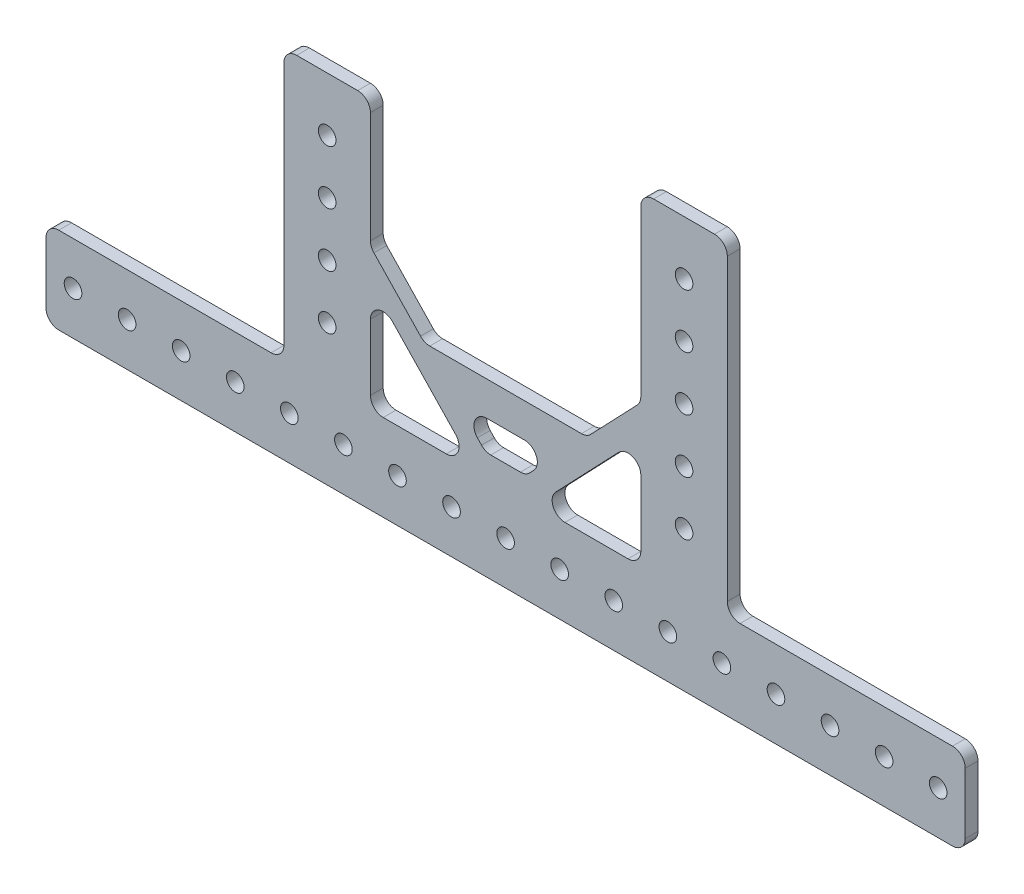
SolidWorks part; units mm, degrees
ref_plane "Front Plane" through (0, 0, 0) normal (0, 0, 1) x (1, 0, 0)
ref_plane "Top Plane" through (0, 0, 0) normal (0, 1, 0) x (1, 0, 0)
ref_plane "Right Plane" through (0, 0, 0) normal (1, 0, 0) x (0, 0, -1)
sketch "Sketch1" plane through (0, 0, 0) normal (0, 0, 1) x (1, 0, 0)
  line L0 (-52.07, 10.16) -> (-31.75, 10.16) construction
  line L1 (-107.95, 10.16) -> (-52.07, 10.16)
  line L2 (-107.95, 10.16) -> (-107.95, -10.16)
  line L3 (-107.95, -10.16) -> (107.95, -10.16)
  line L4 (107.95, 10.16) -> (107.95, -10.16)
  line L5 (-107.95, 10.16) -> (107.95, -10.16) construction
  line L6 (-107.95, -10.16) -> (107.95, 10.16) construction
  line L7 (-52.07, 73.66) -> (-31.75, 73.66)
  line L8 (-52.07, 73.66) -> (-52.07, 10.16)
  line L9 (-52.07, 10.16) -> (-31.75, 10.16) construction
  line L10 (-31.75, 73.66) -> (-31.75, 10.16)
  line L11 (31.75, 86.36) -> (52.07, 86.36)
  line L12 (31.75, 86.36) -> (31.75, 10.16)
  line L13 (31.75, 10.16) -> (52.07, 10.16) construction
  line L14 (52.07, 86.36) -> (52.07, 10.16)
  line L15 (-31.75, 10.16) -> (31.75, 10.16)
  line L16 (31.75, 10.16) -> (52.07, 10.16) construction
  line L17 (52.07, 10.16) -> (107.95, 10.16)
  line L18 (-41.91, 10.16) -> (-41.91, 73.66) construction
  line L19 (0, -55) -> (0, 55) construction
  circle A0 centre (0, 0) radius 2.07
  circle A1 centre (12.7, 0) radius 2.07
  circle A2 centre (25.4, 0) radius 2.07
  circle A3 centre (38.1, 0) radius 2.07
  circle A4 centre (50.8, 0) radius 2.07
  circle A5 centre (63.5, 0) radius 2.07
  circle A6 centre (76.2, 0) radius 2.07
  circle A7 centre (88.9, 0) radius 2.07
  circle A8 centre (101.6, 0) radius 2.07
  circle A9 centre (-12.7, 0) radius 2.07
  circle A10 centre (-25.4, 0) radius 2.07
  circle A11 centre (-38.1, 0) radius 2.07
  circle A12 centre (-50.8, 0) radius 2.07
  circle A13 centre (-63.5, 0) radius 2.07
  circle A14 centre (-76.2, 0) radius 2.07
  circle A15 centre (-88.9, 0) radius 2.07
  circle A16 centre (-101.6, 0) radius 2.07
  circle A17 centre (-41.91, 60.96) radius 2.07
  circle A20 centre (41.91, 60.96) radius 2.07
  circle A21 centre (-41.91, 48.26) radius 2.07
  circle A22 centre (41.91, 48.26) radius 2.07
  circle A23 centre (-41.91, 35.56) radius 2.07
  circle A24 centre (41.91, 35.56) radius 2.07
  circle A25 centre (-41.91, 22.86) radius 2.07
  circle A26 centre (41.91, 22.86) radius 2.07
  circle A27 centre (41.91, 73.66) radius 2.07
  dimension "D1" = 4.14
  dimension "D2" = 20.32
  dimension "D3" = 215.9
  dimension "D4" = 63.5
  dimension "D5" = 31.75
  dimension "D6" = 63.5
  dimension "D8" = 12.7
  dimension "D10" = 12.7
  dimension "D11" = 12.7
  dimension "D13" = 12.7
  dimension "D14" = 76.2
  dimension "D15" = 12.7
  dimension "D7" = 9
  dimension "D9" = 9
  dimension "D12" = 4
extrude "Boss-Extrude1" add sketch "Sketch1" along normal mid plane 3
fillet "Fillet3" radius 3 10 edges at (107.95, -10.16, 0) (-107.95, -10.16, 0) (-107.95, 10.16, 0) (-52.07, 10.16, 0) (-31.75, 10.16, 0) (31.75, 10.16, 0) (52.07, 86.36, 0) (52.07, 10.16, 0) (107.95, 10.16, 0) (-52.07, 73.66, 0)
sketch "Sketch3" plane through (0, 0, 1.5) normal (0, 0, 1) x (1, 0, 0)
  line L0 (-31.75, 43.41) -> (0, 10.16)
  line L1 (-31.75, 13.16) -> (-31.75, 73.66) construction
  line L2 (28.75, 10.16) -> (-28.75, 10.16) construction
  line L3 (0, 10.16) -> (31.75, 43.41)
  line L4 (31.75, 86.36) -> (31.75, 13.16) construction
  line L5 (31.75, 43.41) -> (31.75, 36.17)
  line L6 (6.9134, 10.16) -> (-6.9134, 10.16)
  line L7 (-31.75, 13.16) -> (-31.75, 43.41)
  line L8 (-31.75, 36.17) -> (-6.9134, 10.16)
  line L9 (6.9134, 10.16) -> (31.75, 36.17)
  line L10 (-35.3662, 39.957) -> (-31.75, 36.17) construction
  line L11 (-35.3662, 39.957) -> (0, 2.92) construction
  line L12 (31.75, 36.17) -> (35.3662, 39.957) construction
  line L13 (0, 2.92) -> (35.3662, 39.957) construction
  line L14 (31.75, 86.36) -> (31.75, 43.41) construction
  line L15 (31.75, 36.17) -> (31.75, 13.16) construction
  line L16 (4.7744, 15.16) -> (-4.7744, 15.16)
  line L17 (-6.9134, 10.16) -> (0, 2.92) construction
  line L18 (0, 2.92) -> (6.9134, 10.16) construction
  line L19 (-31.75, 43.41) -> (-31.75, 73.66) construction
  line L20 (28.75, 10.16) -> (6.9134, 10.16) construction
  line L21 (-6.9134, 10.16) -> (-28.75, 10.16) construction
  dimension "D2" = 5
  dimension "D1" = 5
extrude "Boss-Extrude5" add sketch "Sketch3" against normal blind 3
sketch "Sketch4" plane through (0, 0, 1.5) normal (0, 0, 1) x (1, 0, 0)
  line L0 (19.0977, 30.16) -> (-19.0977, 30.16)
  line L1 (4.7744, 15.16) -> (31.75, 43.41) construction
  line L2 (-31.75, 43.41) -> (-4.7744, 15.16) construction
  line L3 (28.75, 10.16) -> (6.9134, 10.16) construction
  line L8 (11.4586, 22.16) -> (19.0977, 30.16)
  line L9 (-19.0977, 30.16) -> (-11.4586, 22.16)
  line L10 (11.4586, 22.16) -> (-11.4586, 22.16)
  line L11 (-31.75, 43.41) -> (-19.0977, 30.16) construction
  line L12 (-11.4586, 22.16) -> (-19.0977, 22.16) construction
  line L13 (19.0977, 22.16) -> (-19.0977, 22.16) construction
  line L14 (-11.4586, 22.16) -> (-4.7744, 15.16) construction
  line L15 (4.7744, 15.16) -> (11.4586, 22.16) construction
  line L16 (19.0977, 22.16) -> (11.4586, 22.16) construction
  line L17 (19.0977, 30.16) -> (31.75, 43.41) construction
  dimension "D1" = 20
  dimension "D2" = 8
extrude "Boss-Extrude6" add sketch "Sketch4" against normal blind 3
fillet "Fillet4" radius 3 14 edges at (31.75, 86.36, 0) (11.4586, 22.16, 0) (-4.7744, 15.16, 0) (-11.4586, 22.16, 0) (4.7744, 15.16, 0) (31.75, 36.17, 0) (6.9134, 10.16, 0) (-31.75, 36.17, 0) (-6.9134, 10.16, 0) (19.0977, 30.16, 0) (31.75, 43.41, 0) (-31.75, 73.66, 0) (-19.0977, 30.16, 0) (-31.75, 43.41, 0)
